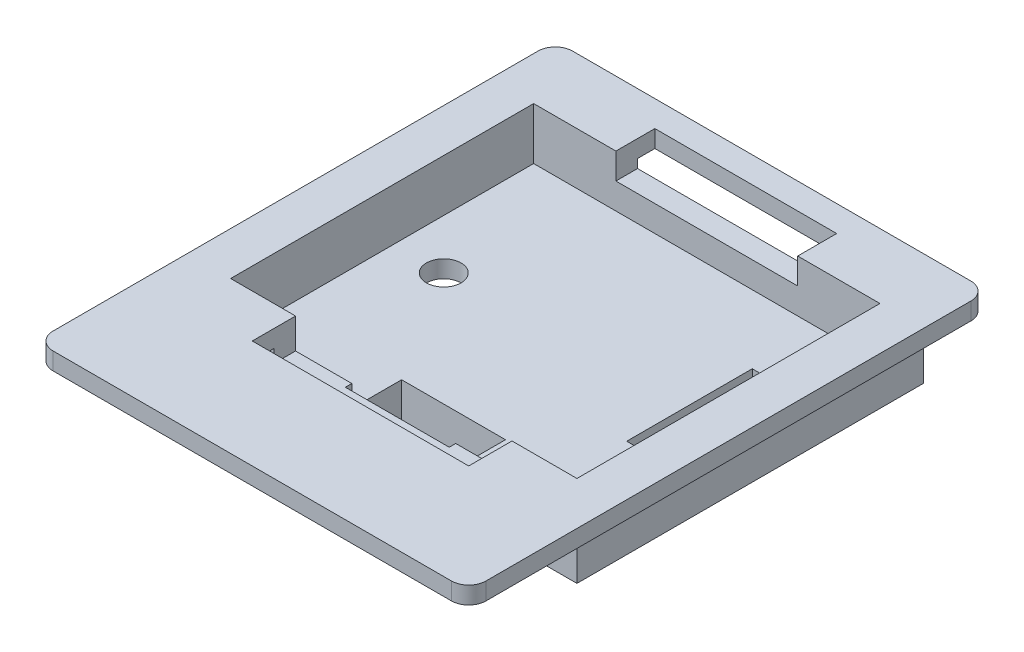
SolidWorks part; units mm, degrees
ref_plane "Front Plane" through (0, 0, 0) normal (0, 0, 1) x (1, 0, 0)
ref_plane "Top Plane" through (0, 0, 0) normal (0, 1, 0) x (1, 0, 0)
ref_plane "Right Plane" through (0, 0, 0) normal (1, 0, 0) x (0, 0, -1)
sketch "Sketch1" plane through (0, 0, 0) normal (0, 1, 0) x (1, 0, 0)
  line L1 (-25, 30) -> (25, 30)
  line L2 (-25, 30) -> (-25, -30)
  line L3 (-25, -30) -> (25, -30)
  line L4 (25, 30) -> (25, -30)
  line L5 (-25, 30) -> (25, -30) construction
  line L6 (-25, -30) -> (25, 30) construction
  point P0 (0, 0)
  dimension "D1" = 60
  dimension "D2" = 50
extrude "Boss-Extrude1" add sketch "Sketch1" along normal blind 15
fillet "Fillet1" radius 2 4 edges at (-25, 7.5, 30) (25, 7.5, 30) (25, 7.5, -30) (-25, 7.5, -30)
sketch "Sketch2" plane through (0, 15, 0) normal (0, 1, 0) x (1, 0, 0)
  line L0 (-20, -12.5) -> (20, -12.5)
  line L1 (-20, 22.5) -> (20, 22.5)
  line L3 (20, -12.5) -> (20, 22.5)
  line L5 (-20, 22.5) -> (20, -22.5) construction
  line L6 (-20, -22.5) -> (20, 22.5) construction
  line L7 (-20, 22.5) -> (-20, -12.5)
  point P0 (0, 0)
  dimension "D1" = 35
  dimension "D2" = 40
extrude "Cut-Extrude1" cut sketch "Sketch2" against normal blind 6
sketch "Sketch3" plane through (0, 9, 0) normal (0, 1, 0) x (1, 0, 0)
  line L0 (16.4, 13.7) -> (13.9, 1) construction
  line L1 (13.9, 1) -> (16.4, 1) construction
  line L2 (16.4, 1) -> (13.9, 13.7) construction
  line L3 (13.9, 13.7) -> (15.15, 7.35) construction
  line L5 (13.15, 14.6) -> (17.15, 14.6)
  line L6 (13.15, 14.6) -> (13.15, 0.1)
  line L7 (13.15, 0.1) -> (17.15, 0.1)
  line L8 (17.15, 14.6) -> (17.15, 0.1)
  line L9 (13.15, 14.6) -> (17.15, 0.1) construction
  line L10 (13.15, 0.1) -> (17.15, 14.6) construction
  dimension "D1" = 14.5
  dimension "D2" = 4
extrude "Cut-Extrude2" cut sketch "Sketch3" against normal blind 10
sketch "Sketch4" plane through (0, 0, 0) normal (0, -1, 0) x (1, 0, 0)
  circle A0 centre (-14.252, -6.369) radius 2
  dimension "D1" = 4
extrude "Cut-Extrude3" cut sketch "Sketch4" against normal blind 10
sketch "Sketch5" plane through (0, 9, 0) normal (0, 1, 0) x (1, 0, 0)
  line L0 (-5.75, -7) -> (5.75, -13) construction
  line L1 (-5.75, -13) -> (5.75, -13) construction
  line L2 (5.75, -13) -> (5.75, -7) construction
  line L3 (5.75, -7) -> (5.75, -13) construction
  line L4 (-5.75, -7) -> (5.75, -7) construction
  line L5 (5.75, -7) -> (-5.75, -13) construction
  line L6 (-5.75, -13) -> (0, -10) construction
  line L8 (-6, -6.75) -> (6, -6.75)
  line L9 (-6, -6.75) -> (-6, -13.25)
  line L10 (-6, -13.25) -> (6, -13.25)
  line L11 (6, -6.75) -> (6, -13.25)
  line L12 (-6, -6.75) -> (6, -13.25) construction
  line L13 (-6, -13.25) -> (6, -6.75) construction
  dimension "D1" = 6.5
  dimension "D2" = 12
extrude "Cut-Extrude4" cut sketch "Sketch5" against normal blind 6 and the other way blind 5
sketch "Sketch6" plane through (0, 0, 0) normal (0, -1, 0) x (1, 0, 0)
  circle A0 centre (0, 10) radius 3.2
  dimension "D1" = 6.4
extrude "Cut-Extrude5" cut sketch "Sketch6" against normal blind 8
sketch "Sketch7" plane through (0, 15, 0) normal (0, 1, 0) x (1, 0, 0)
  line L0 (-20, -12.5) -> (20, -12.5) construction
  line L1 (-12.5, -7.5) -> (12.5, -7.5)
  line L2 (-12.5, -7.5) -> (-12.5, -17.5)
  line L3 (-12.5, -17.5) -> (12.5, -17.5)
  line L4 (12.5, -7.5) -> (12.5, -17.5)
  line L5 (-12.5, -7.5) -> (12.5, -17.5) construction
  line L6 (-12.5, -17.5) -> (12.5, -7.5) construction
  point P0 (0, -12.5)
  dimension "D1" = 10
  dimension "D2" = 25
extrude "Cut-Extrude6" cut sketch "Sketch7" against normal blind 3.5
sketch "Sketch8" plane through (0, 0, 0) normal (0, -1, 0) x (-1, 0, 0)
  line L1 (0, 30) -> (0, 5) construction
  line L2 (-23, 30) -> (23, 30) construction
  line L5 (-22.5, 25) -> (22.5, 25)
  line L6 (-22.5, 25) -> (-22.5, -15)
  line L7 (-22.5, -15) -> (22.5, -15)
  line L8 (22.5, 25) -> (22.5, -15)
  line L9 (-22.5, 25) -> (22.5, -15) construction
  line L10 (-22.5, -15) -> (22.5, 25) construction
  line L11 (-25.6961, 31.0422) -> (25.6961, 31.0422)
  line L12 (-25.6961, 31.0422) -> (-25.6961, -31.0422)
  line L13 (-25.6961, -31.0422) -> (25.6961, -31.0422)
  line L14 (25.6961, 31.0422) -> (25.6961, -31.0422)
  line L15 (-25.6961, 31.0422) -> (25.6961, -31.0422) construction
  line L16 (-25.6961, -31.0422) -> (25.6961, 31.0422) construction
  point P10 (0, 0)
  dimension "D1" = 25
  dimension "D2" = 40
  dimension "D3" = 45
extrude "Cut-Extrude7" cut sketch "Sketch8" against normal blind 13
sketch "Sketch9" plane through (0, 15, 0) normal (0, 1, 0) x (1, 0, 0)
  line L1 (-10.5, 18) -> (10.5, 18)
  line L2 (-10.5, 18) -> (-10.5, 27)
  line L3 (-10.5, 27) -> (10.5, 27)
  line L4 (10.5, 18) -> (10.5, 27)
extrude "Cut-Extrude8" cut sketch "Sketch9" against normal blind 3
sketch "Sketch10" plane through (0, 0, 0) normal (0, -1, 0) x (1, 0, 0)
  line L1 (22.5, 15) -> (7.5, 15)
  line L2 (22.5, -25) -> (-22.5, -25)
  line L3 (22.5, -25) -> (22.5, 15)
  line L4 (22.5, 15) -> (-22.5, 15) construction
  line L6 (-22.5, -25) -> (-22.5, 15)
  line L7 (-22.5, 15) -> (-7.5, 15)
  arc A0 (7.5, 15) -> (-7.5, 15) centre (0, 11) cw
  dimension "D2" = 8.5
  dimension "D1" = 15
extrude "Cut-Extrude9" cut sketch "Sketch10" against normal blind 7
fillet "Fillet2" radius 5 1 edges at (0, 7, 2.5)
